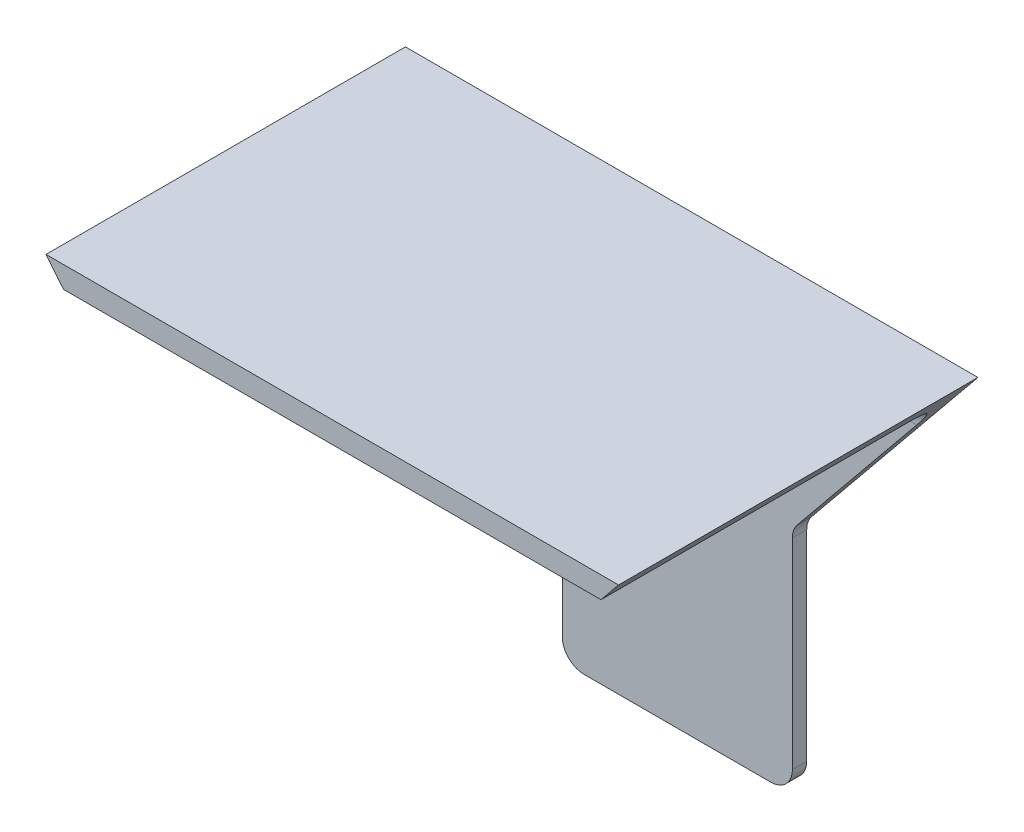
SolidWorks part; units mm, degrees
ref_plane "Front Plane" through (0, 0, 0) normal (0, 0, 1) x (1, 0, 0)
ref_plane "Top Plane" through (0, 0, 0) normal (0, 1, 0) x (1, 0, 0)
ref_plane "Right Plane" through (0, 0, 0) normal (1, 0, 0) x (0, 0, -1)
sketch "Sketch1" plane through (0, 0, 55.6016) normal (0, 0, 1) x (1, 0, 0)
  line L0 (93.8452, 26.6285) -> (21.9446, 26.6285)
  line L12 (44.8949, -34.5432) -> (70.8949, -34.5432)
  line L13 (73.8949, -31.5432) -> (73.8949, -3.6126)
  line L14 (74.5713, -1.715) -> (97.7185, 26.6285)
  line L15 (97.7185, 26.6285) -> (93.8452, 26.6285)
  line L16 (93.8452, 26.6285) -> (72.2477, 0.1826)
  line L17 (70.8949, -3.6126) -> (70.8949, -29.5432)
  line L18 (68.8949, -31.5432) -> (46.8949, -31.5432)
  line L19 (44.8949, -29.5432) -> (44.8949, -3.6126)
  line L20 (43.5421, 0.1826) -> (21.9446, 26.6285)
  line L21 (21.9446, 26.6285) -> (18.0713, 26.6285)
  line L22 (18.0713, 26.6285) -> (41.2185, -1.715)
  line L23 (41.8949, -3.6126) -> (41.8949, -31.5432)
  line L24 (44.8949, -34.5432) -> (70.8949, -34.5432)
  line L25 (73.8949, -31.5432) -> (73.8949, -3.6126)
  line L26 (74.5713, -1.715) -> (97.7185, 26.6285)
  line L27 (97.7185, 26.6285) -> (93.8452, 26.6285)
  line L33 (21.9446, 26.6285) -> (18.0713, 26.6285)
  line L34 (18.0713, 26.6285) -> (41.2185, -1.715)
  line L35 (41.8949, -3.6126) -> (41.8949, -31.5432)
  arc A8 (70.8949, -34.5432) -> (73.8949, -31.5432) centre (70.8949, -31.5432) ccw
  arc A9 (74.5713, -1.715) -> (73.8949, -3.6126) centre (76.8949, -3.6126) ccw
  arc A10 (72.2477, 0.1826) -> (70.8949, -3.6126) centre (76.8949, -3.6126) ccw
  arc A11 (68.8949, -31.5432) -> (70.8949, -29.5432) centre (68.8949, -29.5432) ccw
  arc A12 (44.8949, -29.5432) -> (46.8949, -31.5432) centre (46.8949, -29.5432) ccw
  arc A13 (44.8949, -3.6126) -> (43.5421, 0.1826) centre (38.8949, -3.6126) ccw
  arc A14 (41.8949, -3.6126) -> (41.2185, -1.715) centre (38.8949, -3.6126) ccw
  arc A15 (41.8949, -31.5432) -> (44.8949, -34.5432) centre (44.8949, -31.5432) ccw
  arc A16 (70.8949, -34.5432) -> (73.8949, -31.5432) centre (70.8949, -31.5432) ccw
  arc A17 (74.5713, -1.715) -> (73.8949, -3.6126) centre (76.8949, -3.6126) ccw
  arc A22 (41.8949, -3.6126) -> (41.2185, -1.715) centre (38.8949, -3.6126) ccw
  arc A23 (41.8949, -31.5432) -> (44.8949, -34.5432) centre (44.8949, -31.5432) ccw
  dimension "D1" = 0
extrude "Side extrude" add sketch "Sketch1" along normal blind 2
sketch "Sketch2" plane through (0, 0, 57.6016) normal (0, 0, 1) x (1, 0, 0)
  line L0 (97.7185, 26.6285) -> (18.0713, 26.6285) construction
  line L1 (97.7185, 26.6285) -> (18.0713, 26.6285)
  line L2 (18.0713, 26.6285) -> (20.5213, 23.6285)
  line L3 (18.0713, 26.6285) -> (41.2185, -1.715) construction
  line L4 (20.5213, 23.6285) -> (95.2685, 23.6285)
  line L5 (74.5713, -1.715) -> (97.7185, 26.6285) construction
  line L6 (95.2685, 23.6285) -> (97.7185, 26.6285)
  dimension "D1" = 3
extrude "Top extrude" add sketch "Sketch2" along normal up to surface (48 mm away)
fillet "Fillet between sides 5mm" radius 5 1 edges at (57.8949, 23.6285, 57.6016)
